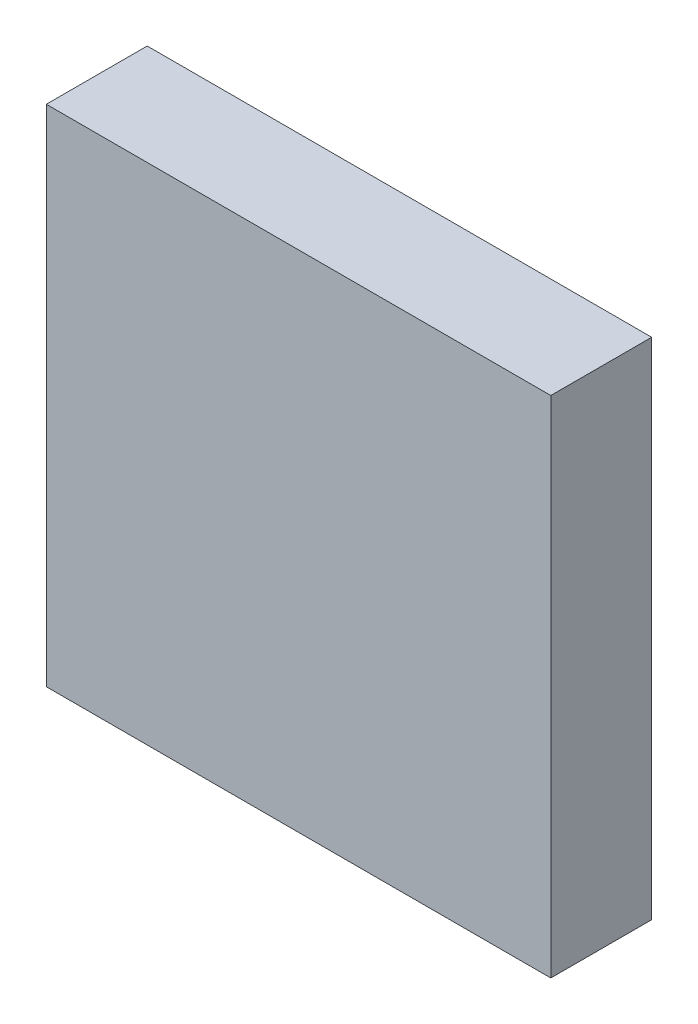
SolidWorks part; units mm, degrees
ref_plane "正面" through (0, 0, 0) normal (0, 0, 1) x (1, 0, 0)
ref_plane "平面" through (0, 0, 0) normal (0, 1, 0) x (1, 0, 0)
ref_plane "右側面" through (0, 0, 0) normal (1, 0, 0) x (0, 0, -1)
sketch "ｽｹｯﾁ1" plane through (0, 0, 0) normal (0, 0, 1) x (1, 0, 0)
  line L1 (0, 0) -> (20, 0)
  line L2 (0, 0) -> (0, 20)
  line L3 (0, 20) -> (20, 20)
  line L4 (20, 0) -> (20, 20)
extrude "ﾎﾞｽ - 押し出し1" add sketch "ｽｹｯﾁ1" along normal blind 4
